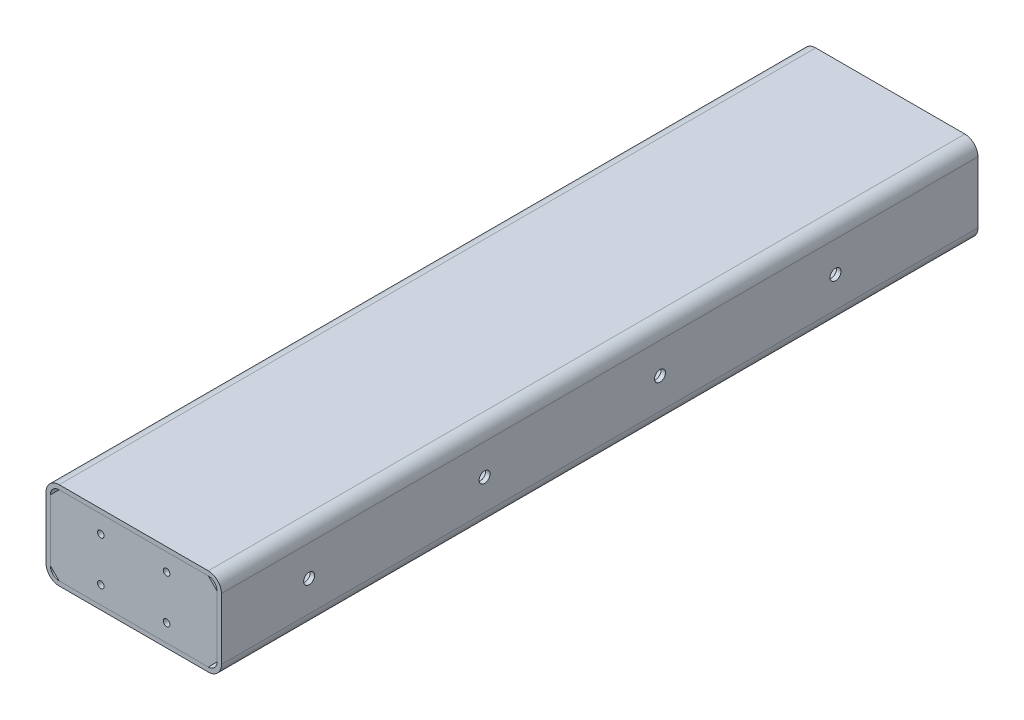
SolidWorks part; units mm, degrees
material "1.0038 (S235JRG2)"
ref_plane "Ebene vorne" through (0, 0, 0) normal (0, 0, 1) x (1, 0, 0)
ref_plane "Ebene oben" through (0, 0, 0) normal (0, 1, 0) x (1, 0, 0)
ref_plane "Ebene rechts" through (0, 0, 0) normal (1, 0, 0) x (0, 0, -1)
sketch "Skizze1" plane through (0, 0, 0) normal (0, 0, 1) x (1, 0, 0)
  line L0 (0, 0) -> (0, 67.8952) construction
  line L1 (-34, 20) -> (34, 20)
  line L2 (0, 0) -> (65.406, 0) construction
  line L3 (40, 14) -> (40, -14)
  line L4 (-40, 14) -> (-40, -14)
  line L5 (-34, -20) -> (34, -20)
  line L6 (-38, 14) -> (-38, -14)
  line L7 (-34, -18) -> (34, -18)
  line L8 (38, 14) -> (38, -14)
  line L9 (-34, 18) -> (34, 18)
  arc A0 (34, 20) -> (40, 14) centre (34, 14) cw
  arc A1 (-34, 20) -> (-40, 14) centre (-34, 14) ccw
  arc A2 (-34, -20) -> (-40, -14) centre (-34, -14) cw
  arc A3 (34, -20) -> (40, -14) centre (34, -14) ccw
  arc A4 (-34, -18) -> (-38, -14) centre (-34, -14) cw
  arc A5 (34, -18) -> (38, -14) centre (34, -14) ccw
  arc A6 (34, 18) -> (38, 14) centre (34, 14) cw
  arc A7 (-34, 18) -> (-38, 14) centre (-34, 14) ccw
  point P12 (40, 0)
  point P13 (0, 20)
  point P19 (-40, 0)
  dimension "D1" = 6
  dimension "D3" = 80
  dimension "D4" = 40
  dimension "D2" = 2
extrude "Aufsatz-Linear austragen1" add sketch "Skizze1" along normal blind 345
sketch "Skizze2" plane through (0, 0, 0) normal (0, 0, -1) x (-1, 0, 0)
  line L0 (38, 14) -> (38, -14) construction
  line L1 (34, -18) -> (-34, -18) construction
  line L2 (-38, -14) -> (-38, 14) construction
  line L3 (-34, 18) -> (34, 18) construction
  line L4 (38, 14) -> (38, -14)
  line L5 (34, -18) -> (-34, -18)
  line L6 (-38, -14) -> (-38, 14)
  line L7 (-34, 18) -> (34, 18)
  line L8 (-38, 14) -> (-34, 18)
  line L9 (34, 18) -> (38, 14)
  line L10 (38, -14) -> (34, -18)
  line L11 (-34, -18) -> (-38, -14)
extrude "Aufsatz-Linear austragen2" add sketch "Skizze2" against normal blind 5 separate body
sketch "Skizze3" plane through (0, 0, 345) normal (0, 0, 1) x (1, 0, 0)
  line L0 (34, 18) -> (38, 14) construction
  line L1 (38, 14) -> (38, -14) construction
  line L2 (38, -14) -> (34, -18) construction
  line L3 (34, -18) -> (-34, -18) construction
  line L4 (-34, -18) -> (-38, -14) construction
  line L5 (-38, 14) -> (-38, -14) construction
  line L6 (-38, 14) -> (-34, 18) construction
  line L7 (-34, 18) -> (34, 18) construction
  line L8 (34, 18) -> (38, 14)
  line L9 (38, 14) -> (38, -14)
  line L10 (38, -14) -> (34, -18)
  line L11 (34, -18) -> (-34, -18)
  line L12 (-34, -18) -> (-38, -14)
  line L13 (-38, 14) -> (-38, -14)
  line L14 (-38, 14) -> (-34, 18)
  line L15 (-34, 18) -> (34, 18)
extrude "Aufsatz-Linear austragen3" add sketch "Skizze3" against normal blind 5 separate body
sketch "Skizze4" plane through (40, 0, 0) normal (1, 0, 0) x (0, 0, -1)
  line L0 (0, 0) -> (-359.732, 0) construction
  line L1 (-345, -14) -> (-345, 14) construction
  circle A0 centre (-305, 0) radius 2.5
  circle A1 centre (-225, 0) radius 2.5
  circle A2 centre (-145, 0) radius 2.5
  circle A3 centre (-65, 0) radius 2.5
  dimension "D1" = 80
  dimension "D2" = 80
  dimension "D3" = 80
  dimension "D4" = 40
  dimension "D5" = 5
extrude "Schnitt-Linear austragen1" cut sketch "Skizze4" against normal blind 100
sketch "Skizze5" plane through (0, 0, 0) normal (0, 0, -1) x (-1, 0, 0)
  line L0 (-42.8183, 0) -> (45.2843, 0) construction
  line L1 (0, 0) -> (0, 28.8923) construction
  circle A0 centre (20, 0) radius 1.5
  circle A1 centre (-20, 0) radius 1.5
  dimension "D1" = 40
  dimension "D2" = 3
extrude "Schnitt-Linear austragen2" cut sketch "Skizze5" against normal blind 10
sketch "Skizze6" plane through (0, 0, 345) normal (0, 0, 1) x (1, 0, 0)
  line L0 (-48.0492, 0) -> (46.181, 0) construction
  line L1 (0, 26.3411) -> (0, -23.5015) construction
  line L2 (-34, -20) -> (34, -20) construction
  circle A0 centre (15, 10) radius 1.5
  circle A1 centre (-15, 10) radius 1.5
  circle A2 centre (15, -10) radius 1.5
  circle A3 centre (-15, -10) radius 1.5
  dimension "D1" = 30
  dimension "D2" = 20
  dimension "D3" = 10
  dimension "D4" = 3
extrude "Schnitt-Linear austragen3" cut sketch "Skizze6" against normal blind 10
